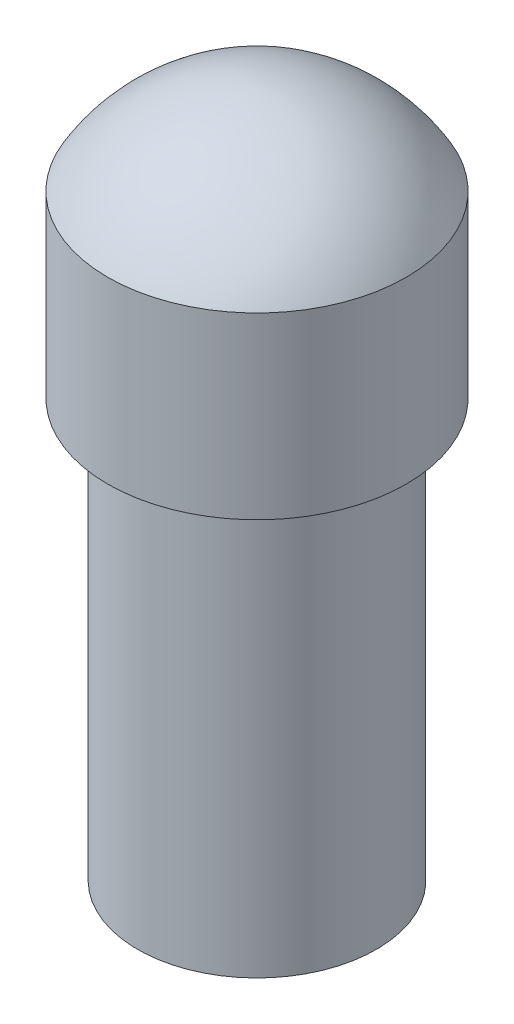
SolidWorks part; units mm, degrees
ref_plane "Front Plane" through (0, 0, 0) normal (0, 0, 1) x (1, 0, 0)
ref_plane "Top Plane" through (0, 0, 0) normal (0, 1, 0) x (1, 0, 0)
ref_plane "Right Plane" through (0, 0, 0) normal (1, 0, 0) x (0, 0, -1)
sketch "Sketch1" plane through (0, 0, 0) normal (0, 0, 1) x (1, 0, 0)
  line L0 (0, 0) -> (0, 23)
  line L1 (5, 20) -> (5, 14)
  line L2 (5, 14) -> (4, 14)
  line L3 (0, 0) -> (4, 0)
  line L4 (4, 0) -> (4, 14)
  arc A3 (0, 23) -> (5, 20) centre (-0.198, 17.0033) cw
  point P5 (2.8889, 22.1482)
  dimension "D4" = 14
  dimension "D1" = 23
  dimension "D2" = 6
  dimension "D3" = 1
  dimension "D5" = 4
  dimension "D6" = 6
revolve "Revolve1" add sketch "Sketch1" angle 360 about L0
ref_plane "Plane1" through (20, 0, 0) normal (1, 0, 0) x (0, 0, -1)
ref_plane "Plane2" through (72, 0, 0) normal (1, 0, 0) x (0, 0, -1)
